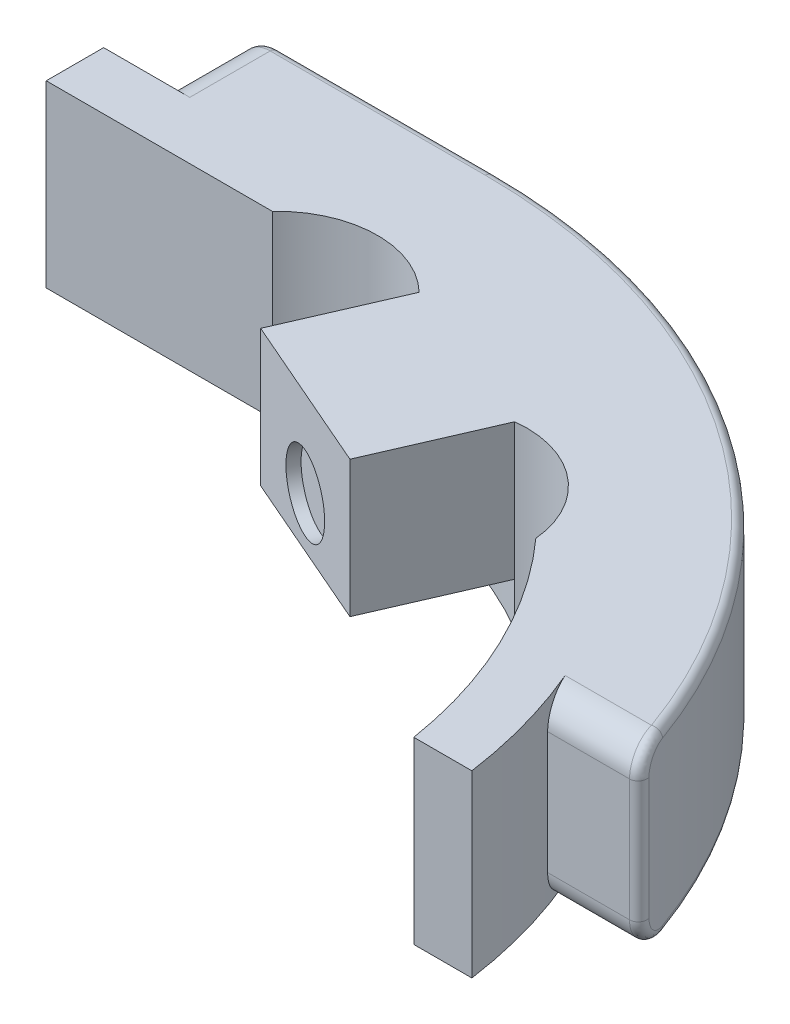
SolidWorks part; units mm, degrees
ref_plane "Front" through (0, 0, 0) normal (0, 0, 1) x (1, 0, 0)
ref_plane "Top" through (0, 0, 0) normal (0, 1, 0) x (1, 0, 0)
ref_plane "Right" through (0, 0, 0) normal (1, 0, 0) x (0, 0, -1)
sketch "Sketch1" plane through (0, 0, 0) normal (0, 1, 0) x (1, 0, 0)
  line L7 (-8.5, 21.5) -> (-8.5, 15.5)
  line L8 (0, 21.5) -> (-8.5, 21.5)
  line L9 (16.6458, 6) -> (-8.5, 15.5)
  line L12 (20.6458, 6) -> (16.6458, 6)
  arc A4 (0, 21.5) -> (20.6458, 6) centre (0, 0) cw
extrude "Boss-Extrude1" add sketch "Sketch1" along normal blind 6.25
sketch "Sketch2" plane through (0, 6.25, 0) normal (0, 1, 0) x (1, 0, 0)
  line L6 (-9.7527, 2.7674) -> (-9.7527, 14.5)
  line L7 (0, 14.5) -> (-9.7527, 14.5)
  line L8 (14.2335, 2.7674) -> (-9.7527, 2.7674)
  arc A2 (14.2335, 2.7674) -> (0, 14.5) centre (0, 0) ccw
extrude "Cut-Extrude1" cut sketch "Sketch2" against normal blind 10
sketch "Sketch3" plane through (0, 6.25, 0) normal (0, 1, 0) x (1, 0, 0)
  line L1 (4.4692, 10.8017) -> (6.3033, 10.0043)
  line L2 (4.4692, 10.8017) -> (2.635, 11.5992)
  line L3 (6.3033, 10.0043) -> (8.4042, 14.8361)
  line L4 (2.635, 11.5992) -> (0.8009, 12.3967)
  line L5 (0.8009, 12.3967) -> (2.8126, 17.0232)
  line L6 (2.8126, 17.0232) -> (8.4042, 14.8361)
extrude "Boss-Extrude2" add sketch "Sketch3" against normal up to surface (6.25 mm away) up to face at (3.7808, 0, -14.022)
sketch "Sketch4" plane through (0, 0, 0) normal (0, -1, 0) x (1, 0, 0)
  line L0 (12.3298, -7.6306) -> (4.8583, -3.0066)
  line L1 (4.8583, -3.0066) -> (-2.1755, -6.7575)
  line L2 (-2.1755, -6.7575) -> (0.3919, -14.4947)
  arc A0 (7.3803, -12.4812) -> (12.3298, -7.6306) centre (0, 0) ccw construction
  arc A1 (0.3919, -14.4947) -> (12.3298, -7.6306) centre (0, 0) ccw
extrude "Cut-Extrude2" cut sketch "Sketch4" against normal blind 1.5
other "Move Face1" face at (3.5521, 3.875, -11.2005) parameters "D1"=0.25
sketch "Sketch5" plane through (4.5609, 0, -10.4893) normal (-0.3987, 0, 0.9171) x (0.9171, 0, 0.3987)
  circle A2 centre (-1.2087, 3.25) radius 1.3
extrude "Cut-Extrude3" cut sketch "Sketch5" against normal blind 0.4
sketch "Sketch6" plane through (0, 6.25, 0) normal (0, 1, 0) x (1, 0, 0)
  line L0 (-8.5, 15.9007) -> (-8.3984, 15.9007)
  line L2 (-8.3984, 17.9007) -> (-8.3984, 15.9007)
  line L3 (-8.3984, 17.9007) -> (-8.5, 17.9007)
  line L5 (-8.5, 15.9007) -> (-10.5, 15.9007)
  line L6 (-10.5, 15.9007) -> (-10.5, 17.9007)
  line L7 (-10.5, 17.9007) -> (-8.5, 17.9007)
extrude "Boss-Extrude3" add sketch "Sketch6" against normal up to surface (6.25 mm away) up to face at (3.7808, 0, -14.022)
other "Move Face2" face at (-4.25, 3.125, -21.5) face at (11.6156, 3.125, -15.4719) parameters "D1"=0.5
sketch "Sketch7" plane through (0, 6.25, 0) normal (0, 1, 0) x (1, 0, 0)
  line L0 (-8.5, 15.9007) -> (0, 15.9007)
  line L1 (6.2036, 9.775) -> (7.2382, 12.1544)
  line L2 (6.2036, 9.775) -> (7.3803, 12.4812) construction
  line L3 (7.2382, 12.1544) -> (7.9427, 13.7748)
  line L4 (0.7012, 12.1675) -> (1.4365, 13.8585)
  line L5 (1.6733, 14.4031) -> (0.7012, 12.1675) construction
  line L6 (1.4365, 13.8585) -> (2.2546, 15.74)
  line L7 (15.8942, 0.4543) -> (-20.8086, -0.5947)
  line L8 (-20.8086, -0.5947) -> (-15.3747, 14.8634)
  line L9 (-15.3747, 14.8634) -> (-8.5, 15.9007)
  line L10 (0.7012, 12.1675) -> (6.2036, 9.775)
  arc A0 (2.2546, 15.74) -> (0, 15.9007) centre (0, 0) ccw
  arc A1 (15.8942, 0.4543) -> (7.9427, 13.7748) centre (0, 0) ccw
extrude "Cut-Extrude4" cut sketch "Sketch7" against normal blind 13
sketch "Sketch8" plane through (0, 0, 0) normal (0, -1, 0) x (1, 0, 0)
  line L0 (14.3393, -6.8714) -> (1.9044, -3.0604)
  line L1 (1.9044, -3.0604) -> (-4.2629, -10.3242)
  line L2 (-4.2629, -10.3242) -> (0.7555, -15.8827)
  arc A0 (7.9427, -13.7748) -> (14.3393, -6.8714) centre (0, 0) ccw construction
  arc A1 (0.7555, -15.8827) -> (14.3393, -6.8714) centre (0, 0) ccw
extrude "Cut-Extrude5" cut sketch "Sketch8" against normal up to surface (1.5 mm away) up to face at (4.0148, 1.5, -12.2816)
sketch "Sketch9" plane through (0, 6.25, 0) normal (0, 1, 0) x (1, 0, 0)
  line L1 (15.7029, 2.5) -> (17.7253, 2.5)
  line L4 (13.2251, 8.8278) -> (15.0867, 9.6347)
  arc A0 (17.7253, 2.5) -> (15.0867, 9.6347) centre (0, 0) ccw
  arc A1 (15.7029, 2.5) -> (13.2251, 8.8278) centre (0, 0) ccw
extrude "Boss-Extrude4" add sketch "Sketch9" against normal up to surface (6.25 mm away) up to face at (1.8778, 0, -14.8757)
sketch "Sketch11" plane through (0, 6.25, 0) normal (0, 1, 0) x (1, 0, 0)
  line L6 (7.9427, 13.7748) -> (11.8277, 10.6272)
  line L8 (0.7012, 12.1675) -> (2.2546, 15.74)
  line L9 (2.2546, 15.74) -> (2.3742, 16.0151)
  line L11 (-10.5, 15.9007) -> (0, 15.9007) construction
  line L12 (-2.6244, 15.9007) -> (0.7012, 12.1675)
  arc A1 (15.7029, 2.5) -> (7.9427, 13.7748) centre (0, 0) ccw construction
  arc A5 (7.9427, 13.7748) -> (11.8277, 10.6272) centre (8.3432, 10.2978) cw
  arc A6 (-2.6244, 15.9007) -> (2.3742, 16.0151) centre (-0.069, 13.5091) cw
extrude "Cut-Extrude6" cut sketch "Sketch11" against normal blind 9
fillet "Fillet1" radius 1 4 edges at (-8.5, 6.25, -19.4503) (-8.5, 0, -19.4503) (18.4949, 0, -6) (18.4949, 6.25, -6)
fillet "Fillet2" radius 0.3 10 edges at (20.017, 6.0097, -6.3497) (20.1246, 3.125, -6) (20.0629, 0.3957, -6.2032) (12.1244, 0, -17.1464) (-3.75, 0, -21) (-8.2071, 0.2929, -21) (-8.5, 3.125, -21) (-8.2071, 5.9571, -21) (-3.75, 6.25, -21) (12.1244, 6.25, -17.1464)
